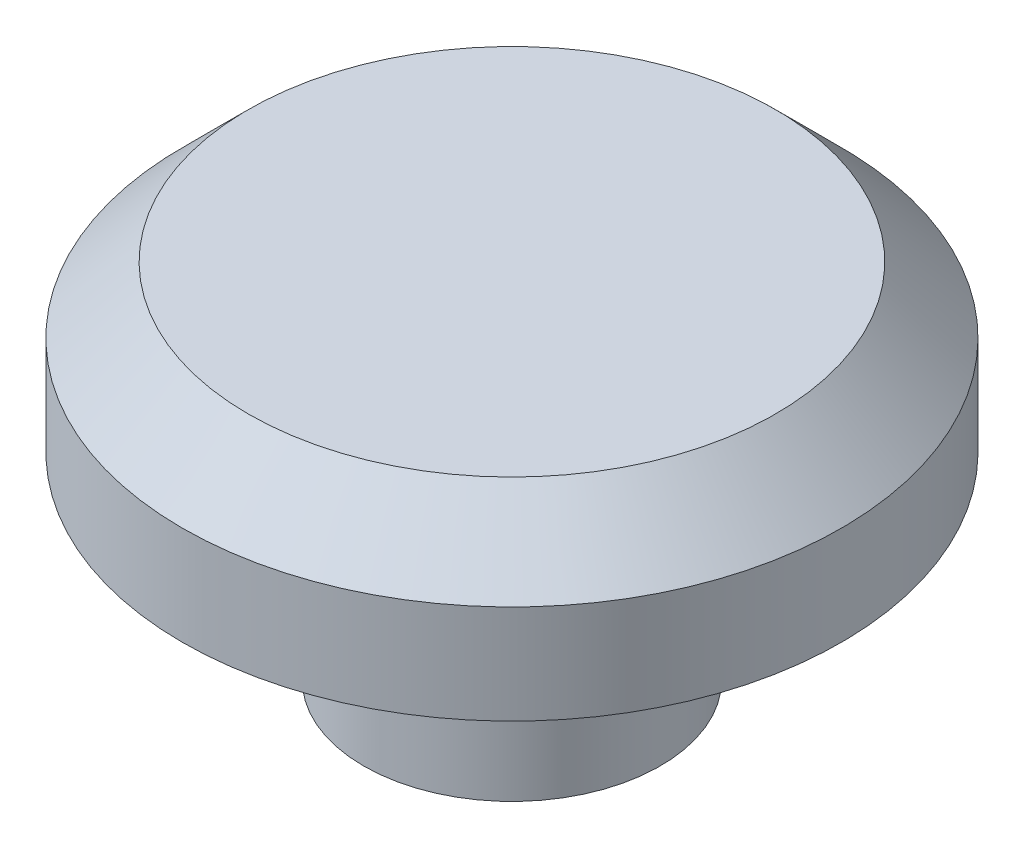
SolidWorks part; units mm, degrees
ref_plane "前基準面" through (0, 0, 0) normal (0, 0, 1) x (1, 0, 0)
ref_plane "上基準面" through (0, 0, 0) normal (0, 1, 0) x (1, 0, 0)
ref_plane "右基準面" through (0, 0, 0) normal (1, 0, 0) x (0, 0, -1)
sketch "草圖2" plane through (0, 0, 0) normal (0, 1, 0) x (1, 0, 0)
  circle A0 centre (0, 0) radius 10
  dimension "D1" = 20
extrude "填料-伸長1" add sketch "草圖2" against normal blind 5
sketch "草圖3" plane through (0, 0, 0) normal (0, 1, 0) x (1, 0, 0)
  circle A0 centre (0, 0) radius 4.5
  dimension "D1" = 9
extrude "填料-伸長2" add sketch "草圖3" against normal blind 11
chamfer "導角1" distance 2 angle 45 1 edges at (0, 0, 10)
